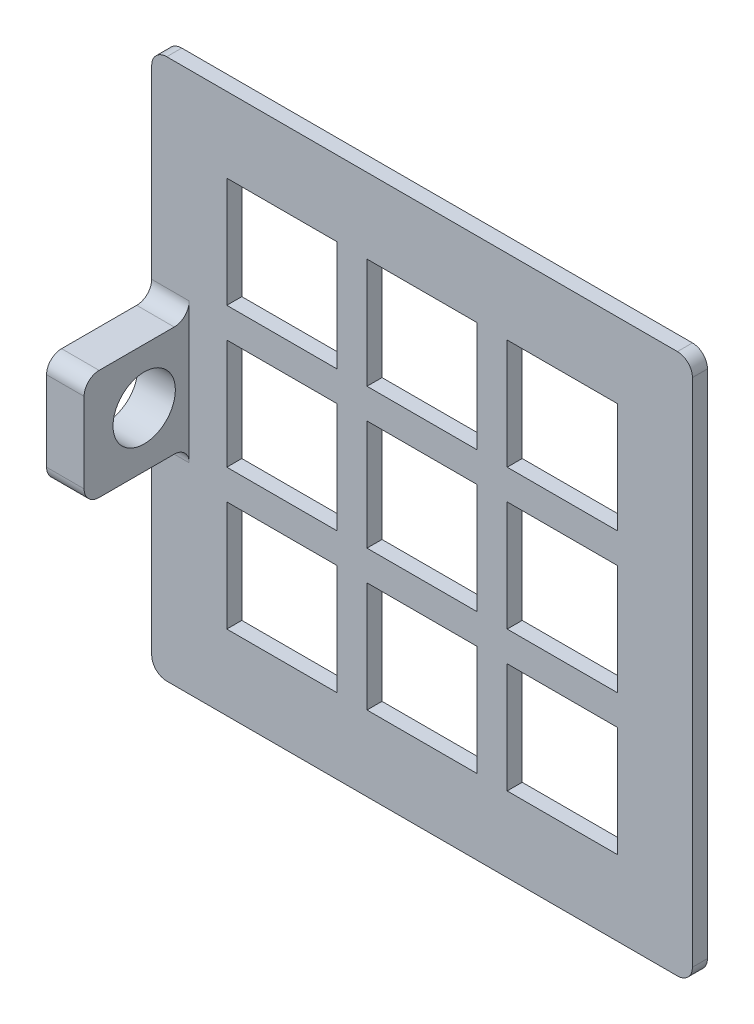
SolidWorks part; units mm, degrees
ref_plane "Front Plane" through (0, 0, 0) normal (0, 0, 1) x (1, 0, 0)
ref_plane "Top Plane" through (0, 0, 0) normal (0, 1, 0) x (1, 0, 0)
ref_plane "Right Plane" through (0, 0, 0) normal (1, 0, 0) x (0, 0, -1)
sketch "Sketch1" plane through (0, 0, 0) normal (0, 0, 1) x (1, 0, 0)
  line L1 (-18, -18) -> (18, -18)
  line L2 (-18, -18) -> (-18, 18)
  line L3 (-18, 18) -> (18, 18)
  line L4 (18, -18) -> (18, 18)
  line L5 (-18, -18) -> (18, 18) construction
  line L6 (-18, 18) -> (18, -18) construction
  point P0 (0, 0)
  dimension "D1" = 36
  dimension "D2" = 36
extrude "Boss-Extrude1" add sketch "Sketch1" along normal blind 10
sketch "Sketch2" plane through (0, 0, 10) normal (0, 0, 1) x (1, 0, 0)
  line L0 (18, 18) -> (-18, 18) construction
  line L1 (-13, -13) -> (13, -13)
  line L2 (-13, -13) -> (-13, 13)
  line L3 (-13, 13) -> (13, 13)
  line L4 (13, -13) -> (13, 13)
  line L5 (-13, -13) -> (13, 13) construction
  line L6 (-13, 13) -> (13, -13) construction
  line L7 (-18, 18) -> (-18, -18) construction
  line L8 (-13, 5.6667) -> (13, 5.6667)
  line L9 (-13, 3.6667) -> (13, 3.6667)
  line L10 (-13, -3.6667) -> (13, -3.6667)
  line L11 (-13, -5.6667) -> (13, -5.6667)
  line L12 (-5.6667, 13) -> (-5.6667, 5.6667)
  line L13 (-5.6667, 5.6667) -> (-5.6667, 3.6667)
  line L14 (-5.6667, 3.6667) -> (-5.6667, -3.6667)
  line L15 (-5.6667, -3.6667) -> (-5.6667, -5.6667)
  line L16 (-5.6667, -5.6667) -> (-5.6667, -13)
  line L17 (-3.6667, 13) -> (-3.6667, 5.6667)
  line L18 (-3.6667, 5.6667) -> (-3.6667, 3.6667)
  line L19 (-3.6667, 3.6667) -> (-3.6667, -3.6667)
  line L20 (-3.6667, -3.6667) -> (-3.6667, -5.6667)
  line L21 (-3.6667, -5.6667) -> (-3.6667, -13)
  line L22 (3.6667, 13) -> (3.6667, 5.6667)
  line L23 (3.6667, 5.6667) -> (3.6667, 3.6667)
  line L24 (3.6667, 3.6667) -> (3.6667, -3.6667)
  line L25 (3.6667, -3.6667) -> (3.6667, -5.6667)
  line L26 (3.6667, -5.6667) -> (3.6667, -13)
  line L27 (5.6667, 13) -> (5.6667, 5.6667)
  line L28 (5.6667, 5.6667) -> (5.6667, 3.6667)
  line L29 (5.6667, 3.6667) -> (5.6667, -3.6667)
  line L30 (5.6667, -3.6667) -> (5.6667, -5.6667)
  line L31 (5.6667, -5.6667) -> (5.6667, -13)
  line L32 (-13, 9.3333) -> (-5.6667, 9.3333) construction
  line L33 (-5.6667, 9.3333) -> (-3.6667, 9.3333) construction
  line L34 (-3.6667, 9.3333) -> (3.6667, 9.3333) construction
  line L35 (3.6667, 9.3333) -> (5.6667, 9.3333) construction
  line L36 (5.6667, 9.3333) -> (13, 9.3333) construction
  point P0 (0, 0)
  dimension "D1" = 5
  dimension "D2" = 5
  dimension "D3" = 2
  dimension "D4" = 2
extrude "Cut-Extrude1" cut sketch "Sketch2" against normal through all contours L12 L3 L2 L8 | L14 L9 L2 L10 | L22 L3 L17 L8 | L24 L9 L19 L10 | L3 L27 L8 L4 | L9 L29 L10 L4 | L11 L31 L1 L4 | L26 L11 L21 L1 | L16 L11 L2 L1
sketch "Sketch6" plane through (0, 0, 0) normal (0, 0, -1) x (-1, 0, 0)
  line L1 (-18, 18) -> (18, 18)
  line L2 (-18, 18) -> (-18, -18)
  line L3 (-18, -18) -> (18, -18)
  line L4 (18, 18) -> (18, -18)
extrude "Cut-Extrude3" cut sketch "Sketch6" against normal offset from surface (7 mm away) 3 up to face at (0, -9.3333, 10)
sketch "Sketch9" plane through (0, 0, 10) normal (0, 0, 1) x (1, 0, 0)
  line L0 (-18, -18) -> (18, -18) construction
  line L1 (-13, -18) -> (18.1973, -18)
  line L2 (-13, -18) -> (-13, 18.1331)
  line L3 (-13, 18.1331) -> (18.1973, 18.1331)
  line L4 (18.1973, -18) -> (18.1973, 18.1331)
extrude "Cut-Extrude5" cut sketch "Sketch9" against normal offset from surface (2 mm away) 1 up to face at (-9.3333, 9.3333, 7)
sketch "Sketch13" plane through (0, 0, 10) normal (0, 0, 1) x (1, 0, 0)
  line L1 (-18, 18) -> (-13, 18)
  line L2 (-18, 18) -> (-18, -18)
  line L3 (-18, -18) -> (-13, -18)
  line L4 (-13, 18) -> (-13, -18)
extrude "Boss-Extrude2" add sketch "Sketch13" along normal blind 10
hole_wizard "Ø4.1 (4.1) Diameter Slot1" positions "Sketch15" profile "Sketch14" size "Ø4.1" standard "ISO" slot yes end condition through all
sketch "Sketch15" plane through (-13, 0, 0) normal (1, 0, 0) x (0, 0, -1)
  line L0 (-8, 5.6667) -> (-8, 3.6667) construction
  point P0 (-11, 0)
  point P2 (-8, 4.6667)
  dimension "D1" = 3
sketch "Sketch14" plane through (-13, 0, 11) normal (0, 1, 0) x (0, 0, -1)
  line L0 (0, 0) -> (0, 5)
  line L1 (0, 5) -> (2.075, 5)
  line L2 (2.075, 5) -> (2.075, 0)
  line L5 (2.075, 0) -> (0, 0)
  line L11 (0, -6.35) -> (0, 107.95) construction
  dimension "Thru Hole Dia." = 4.15
  dimension "Thru Hole Depth" = 5
sketch "Sketch16" plane through (-13, 0, 0) normal (1, 0, 0) x (0, 0, -1)
  line L0 (-8, -18) -> (-8, -3.6667)
  line L1 (-8, -3.6667) -> (-8, -5.6667) construction
  line L2 (-8, -3.6667) -> (-15, -3.6667)
  line L3 (-15, -3.6667) -> (-15, 3.6667)
  line L4 (-15, 3.6667) -> (-8, 3.6667)
  line L5 (-8, 3.6667) -> (-8, 18)
  line L6 (-8, 18) -> (-20, 18)
  line L7 (-20, 18) -> (-20, -18)
  line L8 (-20, -18) -> (-8, -18)
  circle A0 centre (-11, 0) radius 2.075 construction
  dimension "D1" = 4
extrude "Cut-Extrude6" cut sketch "Sketch16" against normal through all
fillet "Fillet1" radius 1 6 edges at (18, -18, 7.5) (-18, -18, 7.5) (18, 18, 7.5) (-18, 18, 7.5) (-15.5, 3.6667, 15) (-15.5, -3.6667, 15)
sketch "Sketch17" plane through (0, 0, 15) normal (0, 0, 1) x (1, 0, 0)
  line L0 (-18, -2.6667) -> (-18, 2.6667) construction
  line L1 (-15.5, 3.6667) -> (-13, 3.6667)
  line L2 (-15.5, 3.6667) -> (-15.5, -3.6667)
  line L3 (-15.5, -3.6667) -> (-13, -3.6667)
  line L4 (-13, 3.6667) -> (-13, -3.6667)
  line L5 (-18, 3.6667) -> (-13, 3.6667) construction
  line L6 (-13, -3.6667) -> (-18, -3.6667) construction
  line L7 (-13, -2.6667) -> (-13, 2.6667) construction
  dimension "D1" = 2.5
extrude "Cut-Extrude7" cut sketch "Sketch17" against normal up to surface (7 mm away)
fillet "Fillet2" radius 1 2 edges at (-16.75, 3.6667, 8) (-16.75, -3.6667, 8)
